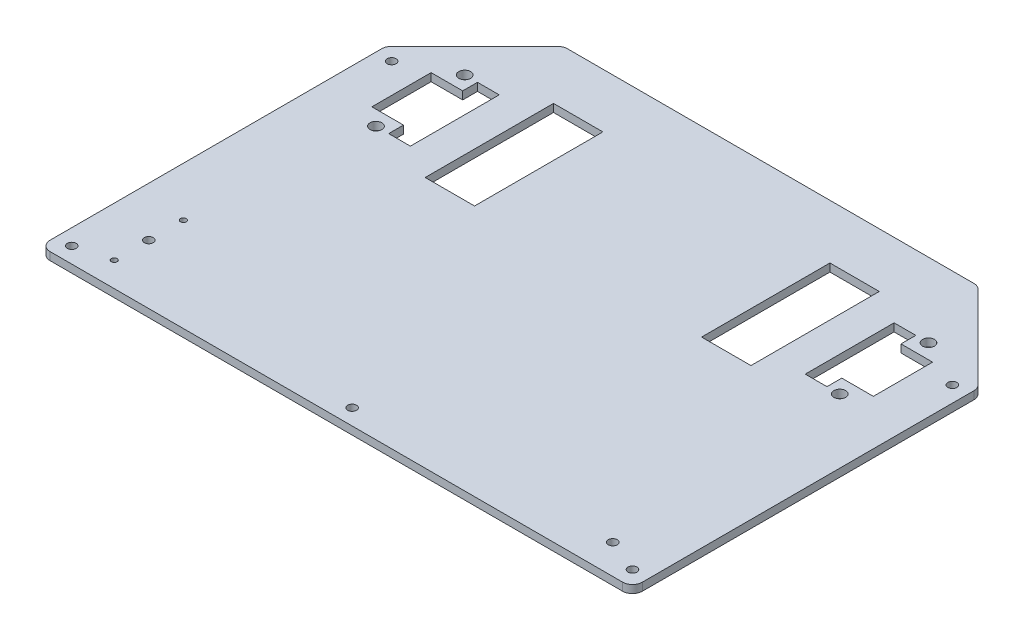
SolidWorks part; units mm, degrees
material "Acier non allié"
ref_plane "Front" through (0, 0, 0) normal (0, 0, 1) x (1, 0, 0)
ref_plane "Top" through (0, 0, 0) normal (0, 1, 0) x (1, 0, 0)
ref_plane "Right" through (0, 0, 0) normal (1, 0, 0) x (0, 0, -1)
sketch "Main scetch" plane through (0, 0, 0) normal (0, 1, 0) x (1, 0, 0)
  line L0 (-150, 0) -> (150, 0)
  line L1 (0, 0) -> (150, 0) construction
  line L2 (0, 0) -> (0, 220) construction
  line L3 (0, 220) -> (150, 220) construction
  line L4 (150, 0) -> (150, 220) construction
  line L5 (150, 0) -> (150, 175)
  line L6 (150, 175) -> (105, 220)
  line L10 (105, 220) -> (-105, 220)
  line L11 (-150, 0) -> (-150, 175)
  line L12 (-150, 175) -> (-105, 220)
  dimension "D1" = 150
  dimension "D2" = 220
  dimension "D3" = 45
  dimension "D4" = 45
extrude "Main extrusion" add sketch "Main scetch" along normal blind 4
fillet "Corner leave" radius 5 6 edges at (-150, 2, 0) (150, 2, -175) (105, 2, -220) (150, 2, 0) (-105, 2, -220) (-150, 2, -175)
sketch "Esquisse2" plane through (0, 4, 0) normal (0, 1, 0) x (1, 0, 0)
  line L0 (-145, 0) -> (145, 0) construction
  line L1 (150, 5) -> (150, 172.9289) construction
  line L2 (148.5355, 176.4645) -> (106.4645, 218.5355) construction
  line L3 (102.9289, 220) -> (-102.9289, 220) construction
  line L4 (-106.4645, 218.5355) -> (-148.5355, 176.4645) construction
  line L5 (-150, 172.9289) -> (-150, 5) construction
  line L6 (-145, 0) -> (145, 0) construction
  line L7 (150, 5) -> (150, 172.9289) construction
  line L8 (148.5355, 176.4645) -> (106.4645, 218.5355) construction
  line L9 (102.9289, 220) -> (-102.9289, 220) construction
  line L10 (-106.4645, 218.5355) -> (-148.5355, 176.4645) construction
  line L11 (-150, 172.9289) -> (-150, 5) construction
  line L12 (0, 0) -> (0, 238.9669) construction
  line L13 (0, 160) -> (165.6987, 160) construction
  line L14 (70, 230.4421) -> (70, 102.0601) construction
  line L15 (57.5, 192.5) -> (82.5, 192.5)
  line L16 (57.5, 192.5) -> (57.5, 127.5)
  line L17 (57.5, 127.5) -> (82.5, 127.5)
  line L18 (82.5, 192.5) -> (82.5, 127.5)
  line L19 (100, 137.5) -> (100, 182.5)
  line L20 (100, 182.5) -> (111, 182.5)
  line L22 (127, 175) -> (127, 145)
  line L23 (100, 137.5) -> (111, 137.5)
  line L35 (111, 182.5) -> (111, 175)
  line L36 (111, 175) -> (127, 175)
  line L37 (111, 137.5) -> (111, 145)
  line L38 (111, 145) -> (127, 145)
  line L39 (-111, 137.5) -> (-111, 145)
  line L40 (-100, 137.5) -> (-111, 137.5)
  line L41 (-100, 137.5) -> (-100, 182.5)
  line L42 (-100, 182.5) -> (-111, 182.5)
  line L43 (-111, 182.5) -> (-111, 175)
  line L44 (-111, 175) -> (-127, 175)
  line L45 (-127, 175) -> (-127, 145)
  line L46 (-111, 145) -> (-127, 145)
  line L47 (-57.5, 127.5) -> (-82.5, 127.5)
  line L48 (-82.5, 192.5) -> (-82.5, 127.5)
  line L49 (-57.5, 192.5) -> (-82.5, 192.5)
  line L50 (-57.5, 192.5) -> (-57.5, 127.5)
  circle A0 centre (117.47, 182.47) radius 3
  circle A1 centre (117.47, 137.53) radius 3
  circle A2 centre (-117.47, 137.53) radius 3
  circle A3 centre (-117.47, 182.47) radius 3
  point P28 (127, 160)
  point P29 (100, 160)
  dimension "D12" = 6
  dimension "D1" = 60
  dimension "D2" = 65
  dimension "D3" = 70
  dimension "D4" = 25
  dimension "D5" = 27
  dimension "D6" = 45
  dimension "D7" = 100
  dimension "D8" = 11
  dimension "D9" = 30
  dimension "D10" = 17.47
  dimension "D11" = 22.47
extrude "Enlèv. mat.-Extru.1" cut sketch "Esquisse2" against normal through all
sketch "Esquisse8" plane through (0, 4, 0) normal (0, 1, 0) x (1, 0, 0)
  line L0 (-150, 172.9289) -> (-150, 5) construction
  line L1 (-145, 0) -> (145, 0) construction
  line L2 (-125, -12.15) -> (-125, 30) construction
  line L3 (150, 5) -> (150, 172.9289) construction
  circle A0 centre (-125, 30) radius 1.5
  circle A1 centre (125, 15) radius 1.5
  circle A2 centre (-125, 12.5) radius 1
  circle A3 centre (-125, 47.5) radius 1
  point P16 (0, 0)
  point P17 (0, 0)
  dimension "D1" = 3
  dimension "D4" = 3
  dimension "D6" = 25
  dimension "D7" = 2
  dimension "D8" = 2
  dimension "D2" = 25
  dimension "D3" = 30
  dimension "D5" = 15
  dimension "D9" = 17.5
  dimension "D10" = 17.5
hole_wizard "Dégagement M41" positions "Esquisse16" profile "Esquisse17" hole size "M4" standard "ISO" end condition through all
sketch "Esquisse16" plane through (0, 4, 0) normal (0, 1, 0) x (1, 0, 0)
  point P0 (-125, 30)
  point P3 (125, 15)
sketch "Esquisse17" plane through (-125, 4, -30) normal (1, 0, 0) x (0, 0, 1)
  line L0 (0, 0) -> (0, 4)
  line L1 (0, 4) -> (2.25, 4)
  line L2 (2.25, 4) -> (2.25, 0)
  line L5 (2.25, 0) -> (0, 0)
  line L11 (0, -6.35) -> (0, 107.95) construction
  dimension "Diamètre du perçage jusqu'au prochain" = 4.5
  dimension "Profondeur du perçage jusqu'au prochain" = 4
sketch "Esquisse18" plane through (0, 4, 0) normal (0, 1, 0) x (1, 0, 0)
  line L0 (-150, 172.9289) -> (-150, 5) construction
  line L1 (-145, 0) -> (145, 0) construction
  line L3 (150, 5) -> (150, 172.9289) construction
  line L4 (0, 0) -> (0, 20.6924) construction
  circle A0 centre (-142, 8) radius 1
  circle A1 centre (-142, 170) radius 1
  circle A4 centre (142, 170) radius 1
  circle A5 centre (142, 8) radius 1
  circle A6 centre (0, 8) radius 1.5
  dimension "D1" = 2
  dimension "D2" = 2
  dimension "D3" = 3
  dimension "D4" = 8
  dimension "D5" = 2
  dimension "D6" = 2
  dimension "D7" = 8
  dimension "D8" = 8
  dimension "D9" = 170
  dimension "D10" = 8
  dimension "D15" = 8
  dimension "D16" = 170
  dimension "D17" = 8
  dimension "D18" = 8
hole_wizard "Dégagement M42" positions "Esquisse19" profile "Esquisse20" hole size "M4" standard "ISO" end condition through all
sketch "Esquisse19" plane through (0, 4, 0) normal (0, 1, 0) x (1, 0, 0)
  point P0 (-142, 8)
  point P3 (0, 8)
  point P6 (142, 8)
  point P9 (142, 170)
  point P12 (-142, 170)
sketch "Esquisse20" plane through (-142, 4, -8) normal (1, 0, 0) x (0, 0, 1)
  line L0 (0, 0) -> (0, 4)
  line L1 (0, 4) -> (2.25, 4)
  line L2 (2.25, 4) -> (2.25, 0)
  line L5 (2.25, 0) -> (0, 0)
  line L11 (0, -6.35) -> (0, 107.95) construction
  dimension "Diamètre du perçage jusqu'au prochain" = 4.5
  dimension "Profondeur du perçage jusqu'au prochain" = 4
hole_wizard "Dégagement M2.51" positions "Esquisse21" profile "Esquisse22" hole size "M2.5" standard "ISO" end condition through all
sketch "Esquisse21" plane through (0, 4, 0) normal (0, 1, 0) x (1, 0, 0)
  point P0 (-125, 47.5)
  point P3 (-125, 12.5)
sketch "Esquisse22" plane through (-125, 4, -47.5) normal (1, 0, 0) x (0, 0, 1)
  line L0 (0, 0) -> (0, 4)
  line L1 (0, 4) -> (1.45, 4)
  line L2 (1.45, 4) -> (1.45, 0)
  line L5 (1.45, 0) -> (0, 0)
  line L11 (0, -6.35) -> (0, 107.95) construction
  dimension "Diamètre du perçage jusqu'au prochain" = 2.9
  dimension "Profondeur du perçage jusqu'au prochain" = 4
equation "\"WIDTH\"= 300mm'Total width of the robot"
equation "\"LENGTH\"= 220mm'Total length of the robot"
equation "\"D1@Main scetch\" = \"WIDTH\" / 2"
equation "\"D2@Main scetch\" = \"LENGTH\""
equation "\"CUT_DEPTH\"= 45mm'Depth of the cut on the edges of the plate"
equation "\"D3@Main scetch\" = \"CUT_DEPTH\""
equation "\"D4@Main scetch\" = \"CUT_DEPTH\""
equation "\"Plate_th\"= 3mm'Thickness of the plate"
equation "\"D1\"= \"Plate_th\""
